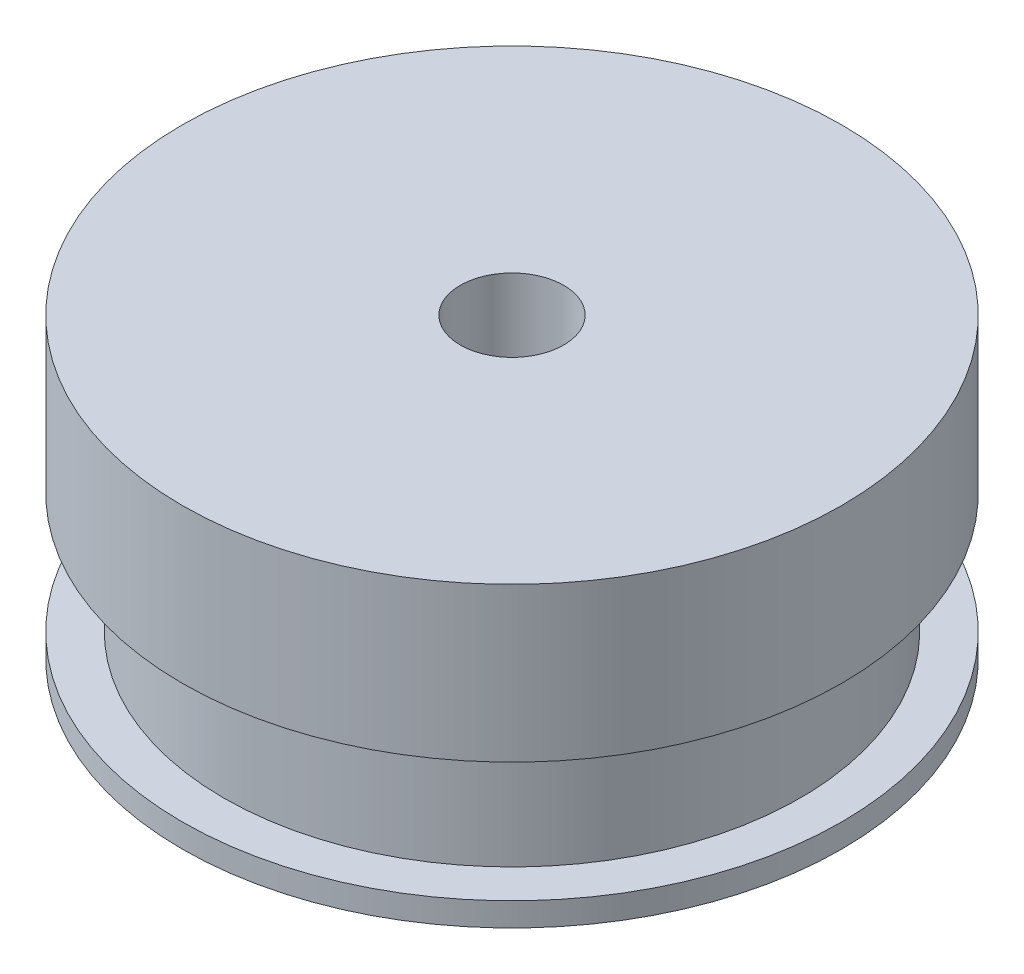
SolidWorks part; units mm, degrees
ref_plane "Front Plane" through (0, 0, 0) normal (0, 0, 1) x (1, 0, 0)
ref_plane "Top Plane" through (0, 0, 0) normal (0, 1, 0) x (1, 0, 0)
ref_plane "Right Plane" through (0, 0, 0) normal (1, 0, 0) x (0, 0, -1)
sketch "Sketch1" plane through (0, 0, 0) normal (0, 1, 0) x (1, 0, 0)
  circle A0 centre (0, 0) radius 20.2311
  circle A1 centre (0, 0) radius 3.175
  dimension "D1" = 40.4622
  dimension "D2" = 6.35
extrude "Boss-Extrude1" add sketch "Sketch1" along normal blind 18.2626
ref_axis "Axis1" through (0, 18.2626, 0) along (0, -1, 0)
sketch "Sketch2" plane through (0, 0, 0) normal (1, 0, 0) x (0, 0, -1)
  line L0 (20.2311, 1.4478) -> (17.6911, 1.4478)
  line L1 (17.6911, 1.4478) -> (17.6911, 8.8138)
  line L2 (17.6911, 8.8138) -> (20.2311, 8.8138)
  line L3 (20.2311, 0) -> (20.2311, 18.2626) construction
  line L4 (20.2311, 8.8138) -> (20.2311, 1.4478)
  line L5 (-20.2311, 0) -> (20.2311, 0) construction
  dimension "D1" = 7.366
  dimension "D2" = 2.54
  dimension "D3" = 1.4478
revolve "Cut-Revolve1" cut sketch "Sketch2" angle 360 about axis through (0, 18.2626, 0) along (0, -1, 0)
